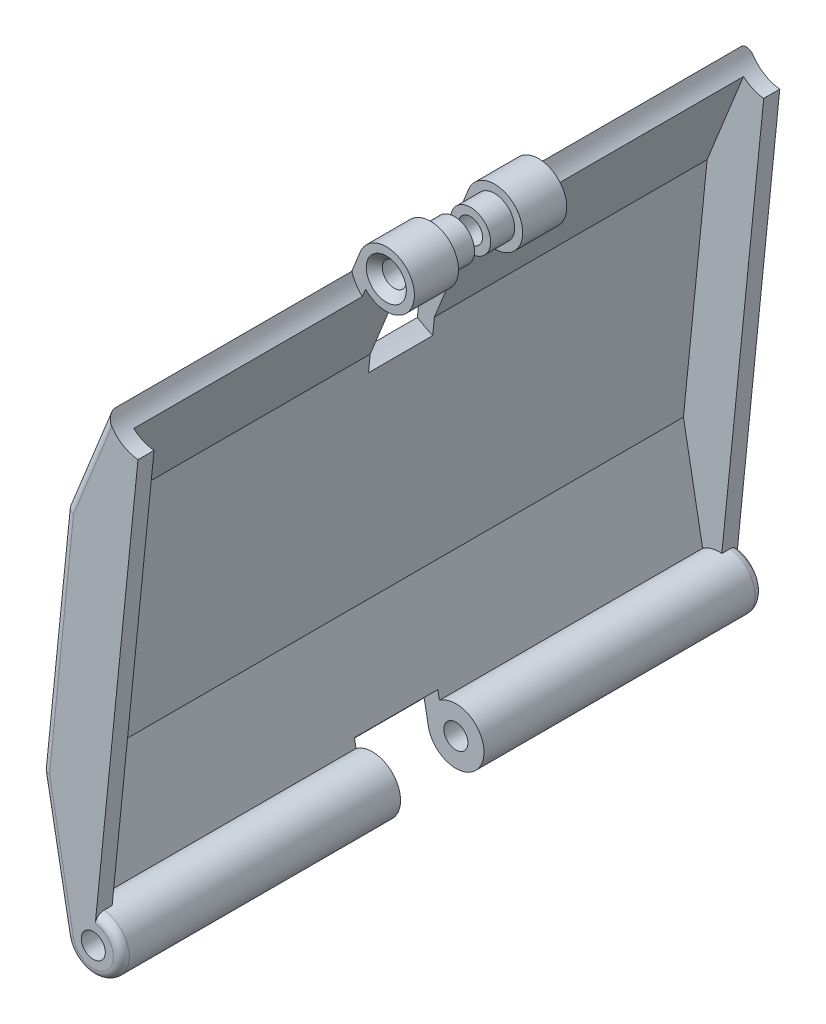
SolidWorks part; units mm, degrees
ref_plane "Alzado" through (0, 0, 0) normal (0, 0, 1) x (1, 0, 0)
ref_plane "Planta" through (0, 0, 0) normal (0, 1, 0) x (1, 0, 0)
ref_plane "Vista lateral" through (0, 0, 0) normal (1, 0, 0) x (0, 0, -1)
sketch "General" plane through (0, 0, 0) normal (0, 0, 1) x (1, 0, 0)
  line L0 (0, 0) -> (0, 6925.6593) construction
  line L1 (0, 0) -> (6925.6593, 0) construction
  line L2 (-78.0143, 29.5019) -> (-58.2048, 32.2552) construction
  line L3 (-58.2048, 32.2552) -> (-20, 0) construction
  line L4 (-20, 0) -> (-84.0374, -30.1951) construction
  line L5 (-84.0374, -30.1951) -> (-78.0143, 29.5019) construction
  line L6 (-65.088, 81.7791) -> (-58.2048, 32.2552) construction
  line L7 (-78.0143, 29.5019) -> (-65.088, 81.7791) construction
  line L8 (-84.0374, -30.1951) -> (-35.25, -19.25) construction
  line L9 (65.1803, -5) -> (-49934.8197, -5) construction
  line L10 (0, 20) -> (0, 30) construction
  line L11 (-46.5, -33.5) -> (0, -33.5) construction
  line L12 (-46.5, -33.5) -> (-46.5, -5) construction
  line L13 (-46.5, -5) -> (0, -5) construction
  line L14 (0, -33.5) -> (0, -5) construction
  line L15 (-46.5, -33.5) -> (0, -5) construction
  line L16 (-46.5, -5) -> (0, -33.5) construction
  line L17 (-20, 20) -> (-20, 30) construction
  line L18 (20, 20) -> (20, 30) construction
  line L19 (0, 45) -> (0, 35) construction
  line L20 (35, 45) -> (35, 35) construction
  line L21 (-35, 45) -> (-35, 35) construction
  line L22 (-65.088, 81.7791) -> (-73.0652, 87.8094)
  line L23 (-62.6266, 21.5923) -> (-35.5012, -1.3089)
  line L24 (-46.1985, 7.7225) -> (-39.1024, 16.1276) construction
  line L25 (-62.6266, 21.5923) -> (-63.6587, 20.3697)
  line L26 (-63.6587, 20.3697) -> (-36.5334, -2.5315)
  line L27 (-36.5334, -2.5315) -> (-35.5012, -1.3089)
  line L28 (-77.8743, 85.4238) -> (-78.0143, 29.5019)
  circle A0 centre (-20, 0) radius 1.5
  circle A1 centre (-58.2048, 32.2552) radius 1.5
  circle A2 centre (-78.0143, 29.5019) radius 1.5 construction
  circle A3 centre (-84.0374, -30.1951) radius 1.5
  circle A4 centre (-65.088, 81.7791) radius 1.5 construction
  arc A5 (-65.088, 81.7791) -> (-58.2048, 32.2552) centre (13.6235, 67.4788) ccw
  arc A6 (-58.2048, 32.2552) -> (-20, 0) centre (9.9212, 74.1938) ccw
  circle A7 centre (-35.25, -19.25) radius 10 construction
  arc A8 (-20, 20) -> (20, 20) centre (0, 20) ccw construction
  arc A9 (20, 30) -> (-20, 30) centre (0, 30) ccw construction
  arc A10 (-20, 0) -> (0, -2.5403) centre (0, 77.4597) ccw
  arc A11 (35, 45) -> (-35, 45) centre (0, 45) ccw construction
  arc A12 (-35, 35) -> (35, 35) centre (0, 35) ccw construction
  circle A13 centre (-58.2048, 32.2552) radius 3.5
  circle A14 centre (-20, 0) radius 3.5
  circle A15 centre (-78.0143, 29.5019) radius 3.5
  circle A16 centre (-84.0374, -30.1951) radius 3.5
  arc A17 (-73.0652, 87.8094) -> (-77.8743, 85.4238) centre (-74.8743, 85.4163) ccw
  arc A18 (-67.2644, 17.1116) -> (-32.3067, -12.0199) centre (9.9212, 74.1938) ccw
  point P19 (-23.25, -19.25)
  point P26 (0, 25)
  point P35 (0, 40)
  dimension "D1" = 40
  dimension "D2" = 3
  dimension "D3" = 50
  dimension "D4" = 50
  dimension "D7" = 80
  dimension "D8" = 80
  dimension "D10" = 35.25
  dimension "D17" = 20
  dimension "D18" = 80
  dimension "D20" = 35
  dimension "D21" = 20
  dimension "D24" = 7
  dimension "D25" = 1.6
  dimension "D27" = 3
  dimension "D28" = 16
  dimension "D5" = 20
  dimension "D6" = 90
  dimension "D9" = 60
  dimension "D11" = 14.25
  dimension "D12" = 50
  dimension "D13" = 5
  dimension "D14" = 46.5
  dimension "D15" = 28.5
  dimension "D16" = 10
  dimension "D19" = 10
  dimension "D22" = 135
  dimension "D23" = 10
  dimension "D26" = 11
  dimension "D29" = 35.5
  dimension "D30" = 14
sketch "Croquis2" plane through (0, 0, 0) normal (0, 0, 1) x (1, 0, 0)
  line L4 (-81.2606, 30.8103) -> (-87.4797, 15.3807)
  line L5 (-87.4797, 15.3807) -> (-90.4912, -14.4678)
  line L6 (-90.4912, -14.4678) -> (-87.4795, -30.8287)
  line L11 (-78.3657, 26.0195) -> (-83.686, -26.7127)
  line L12 (-58.6933, 31.6675) -> (-20403.1678, -45642.202) construction
  line L13 (-58.6933, 31.6675) -> (-31726.1656, -38661.6291) construction
  line L17 (-84.0374, -30.1951) -> (-78.0143, 29.5019) construction
  line L18 (-76.6758, -0.7855) -> (-49286.5948, 4964.1562) construction
  circle A18 centre (-78.0143, 29.5019) radius 3.5 construction
  circle A19 centre (-84.0374, -30.1951) radius 3.5 construction
  arc A20 (-81.2606, 30.8103) -> (-78.3657, 26.0195) centre (-78.0143, 29.5019) cw
  arc A21 (-87.4795, -30.8287) -> (-83.686, -26.7127) centre (-84.0374, -30.1951) ccw
  circle A22 centre (-78.0143, 29.5019) radius 1.5
  circle A23 centre (-84.0374, -30.1951) radius 1.5
  point P21 (-81.0258, -0.3466)
  point P24 (-88.9854, 0.4565)
  dimension "D1" = 3
  dimension "D3" = 30
  dimension "D2" = 8
extrude "Saliente-Extruir1" add sketch "Croquis2" along normal blind 40
sketch "Croquis20" plane through (0, 0, 0) normal (0, 0, -1) x (-1, 0, 0)
  line L0 (80.5878, 27.1296) -> (85.5183, 14.8969)
  line L1 (85.5183, 14.8969) -> (88.4727, -14.3855)
  line L2 (88.4727, -14.3855) -> (86.0851, -27.3566)
  line L3 (78.3657, 26.0195) -> (83.686, -26.7127)
  line L4 (81.2606, 30.8103) -> (87.4797, 15.3807) construction
  line L5 (87.4797, 15.3807) -> (90.4912, -14.4678) construction
  line L6 (90.4912, -14.4678) -> (87.4795, -30.8287) construction
  arc A0 (78.3657, 26.0195) -> (80.5878, 27.1296) centre (78.0143, 29.5019) ccw
  circle A1 centre (84.0374, -30.1951) radius 3.5 construction
  arc A2 (83.686, -26.7127) -> (86.0851, -27.3566) centre (84.0374, -30.1951) cw
  dimension "D1" = 2
  dimension "D2" = 2
  dimension "D3" = 2
extrude "Cortar-Extruir8" cut sketch "Croquis20" against normal offset from surface (38 mm away) 2 up to face at (-83.3082, -0.1163, 40)
sketch "Croquis21" plane through (0, 0, 40) normal (0, 0, 1) x (1, 0, 0)
  circle A0 centre (-78.0143, 29.5019) radius 4.5
  circle A1 centre (-78.0143, 29.5019) radius 3.5 construction
  dimension "D1" = 1
extrude "Cortar-Extruir9" cut sketch "Croquis21" against normal offset from surface (30.5 mm away) 9.5 up to face at (-84.3787, -0.0083, 0)
chamfer "Chaflán1" distance 1 angle 45 1 edges at (-79.5143, 29.5019, 9.5)
sketch "Croquis22" plane through (0, 0, 0) normal (0, 0, -1) x (-1, 0, 0)
  circle A0 centre (78.0143, 29.5019) radius 18.418
extrude "Cortar-Extruir10" cut sketch "Croquis22" against normal blind 4
sketch "Croquis23" plane through (0, 0, 4) normal (0, 0, -1) x (-1, 0, 0)
  circle A0 centre (78.0143, 29.5019) radius 1.5
  circle A1 centre (78.0143, 29.5019) radius 2.5
  dimension "D1" = 1
extrude "Saliente-Extruir2" add sketch "Croquis23" along normal blind 3
sketch "Croquis24" plane through (0, 0, 0) normal (0, 0, -1) x (-1, 0, 0)
  circle A0 centre (84.0374, -30.1951) radius 4.5
  arc A1 (86.0851, -27.3566) -> (87.4795, -30.8287) centre (84.0374, -30.1951) ccw construction
  dimension "D1" = 1
extrude "Cortar-Extruir11" cut sketch "Croquis24" against normal blind 5.2
mirror "Simetría1" about plane through (-78.0143, 29.5019, 0) normal (0, 0, -1) of bodies 120 103
fillet "Redondeo Cable plano" radius 1 8 edges at (-81.4637, -32.5671, -40) (-81.4637, -32.5671, 40) (-88.9854, -22.6482, -40) (-88.9854, 0.4565, -40) (-84.8988, 21.7838, -40) (-88.9854, -22.6482, 40) (-84.8988, 21.7838, 40) (-88.9854, 0.4565, 40)
